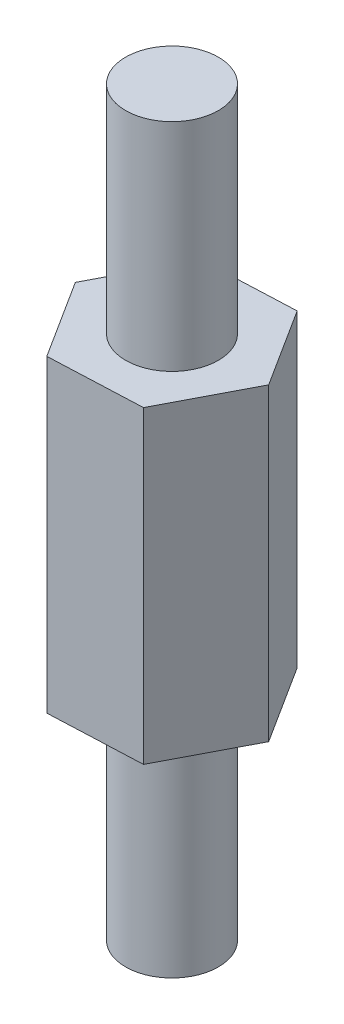
SolidWorks part; units mm, degrees
ref_plane "Front Plane" through (0, 0, 0) normal (0, 0, 1) x (1, 0, 0)
ref_plane "Top Plane" through (0, 0, 0) normal (0, 1, 0) x (1, 0, 0)
ref_plane "Right Plane" through (0, 0, 0) normal (1, 0, 0) x (0, 0, -1)
sketch "Sketch3" plane through (0, 0, 0) normal (0, 1, 0) x (1, 0, 0)
  line L1 (1.389, 2.6622) -> (-1.611, 2.534)
  line L2 (-1.611, 2.534) -> (-3, -0.1282)
  line L3 (-3, -0.1282) -> (-1.389, -2.6622)
  line L4 (-1.389, -2.6622) -> (1.611, -2.534)
  line L5 (1.611, -2.534) -> (3, 0.1282)
  line L6 (3, 0.1282) -> (1.389, 2.6622)
  circle A0 centre (0, 0) radius 2.6004 construction
  dimension "D2" = 5.2009
  dimension "D1" = 6
extrude "Boss-Extrude1" add sketch "Sketch3" along normal blind 10
sketch "Sketch4" plane through (0, 10, 0) normal (0, 1, 0) x (1, 0, 0)
  circle A0 centre (0, 0) radius 1.5
  dimension "D1" = 3
extrude "Boss-Extrude2" add sketch "Sketch4" along normal blind 7
sketch "Sketch5" plane through (0, 0, 0) normal (0, -1, 0) x (1, 0, 0)
  circle A0 centre (0, 0) radius 1.5
  dimension "D1" = 3
extrude "Boss-Extrude3" add sketch "Sketch5" along normal blind 7
